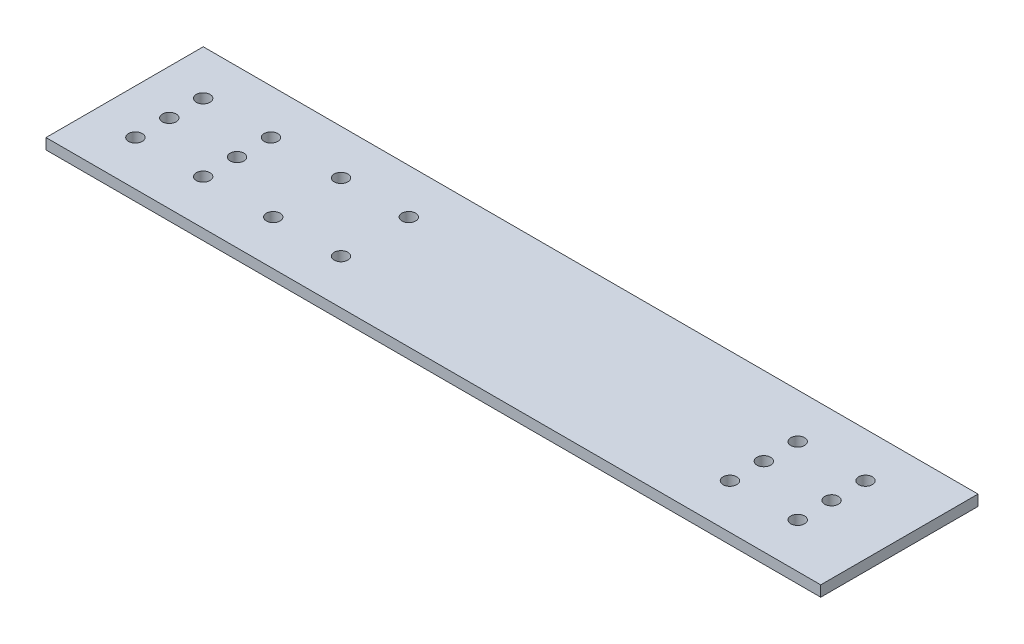
SolidWorks part; units mm, degrees
material "AISI Type A2 Tool Steel"
ref_plane "Front Plane" through (0, 0, 0) normal (0, 0, 1) x (1, 0, 0)
ref_plane "Top Plane" through (0, 0, 0) normal (0, 1, 0) x (1, 0, 0)
ref_plane "Right Plane" through (0, 0, 0) normal (1, 0, 0) x (0, 0, -1)
sketch "Sketch1" plane through (0, 0, 0) normal (0, 1, 0) x (1, 0, 0)
  line L0 (-46.35, 46.4) -> (410.85, 46.4)
  line L1 (-20, 20) -> (20, 20) construction
  line L2 (-20, 20) -> (-20, -20) construction
  line L3 (-20, -20) -> (20, -20) construction
  line L4 (20, 20) -> (20, -20) construction
  line L5 (-20, 20) -> (20, -20) construction
  line L6 (-20, -20) -> (20, 20) construction
  line L8 (-46.35, 46.4) -> (-46.35, -46.4)
  line L11 (410.85, 46.4) -> (410.85, -46.4)
  line L12 (410.85, -46.4) -> (-46.35, -46.4)
  line L13 (350.85, 0) -> (0, 0) construction
  line L14 (370.85, -20) -> (330.85, -20) construction
  line L15 (370.85, -20) -> (370.85, 20) construction
  line L16 (370.85, 20) -> (330.85, 20) construction
  line L17 (330.85, -20) -> (330.85, 20) construction
  line L18 (370.85, -20) -> (330.85, 20) construction
  line L19 (370.85, 20) -> (330.85, -20) construction
  line L20 (81.35, 0) -> (81.35, 30.8998) construction
  line L25 (-40, 40) -> (40, 40) construction
  line L26 (310.85, -40) -> (390.85, -40) construction
  line L31 (-40, 40) -> (-40, -40) construction
  line L32 (-40, -40) -> (40, -40) construction
  line L33 (310.85, -40) -> (310.85, 40) construction
  line L34 (310.85, 40) -> (390.85, 40) construction
  line L35 (390.85, -40) -> (390.85, 40) construction
  line L36 (310.85, -40) -> (390.85, 40) construction
  line L37 (310.85, 40) -> (390.85, -40) construction
  line L38 (278.85, -20) -> (238.85, -20) construction
  line L39 (278.85, -20) -> (278.85, 20) construction
  line L40 (278.85, 20) -> (238.85, 20) construction
  line L41 (238.85, -20) -> (238.85, 20) construction
  line L42 (278.85, -20) -> (238.85, 20) construction
  line L43 (278.85, 20) -> (238.85, -20) construction
  line L48 (40, 40) -> (40, -40) construction
  line L49 (-40, 40) -> (40, -40) construction
  line L50 (-40, -40) -> (40, 40) construction
  line L51 (61.35, -20) -> (101.35, -20) construction
  line L52 (61.35, -20) -> (61.35, 20) construction
  line L53 (61.35, 20) -> (101.35, 20) construction
  line L54 (101.35, -20) -> (101.35, 20) construction
  line L55 (61.35, -20) -> (101.35, 20) construction
  line L56 (61.35, 20) -> (101.35, -20) construction
  line L57 (46.35, 30.8998) -> (116.35, 30.8998) construction
  line L58 (46.35, 30.8998) -> (46.35, -40.05) construction
  line L59 (46.35, -40.05) -> (116.35, -40.05) construction
  line L60 (116.35, 30.8998) -> (116.35, -40.05) construction
  circle A0 centre (-20, 20) radius 4.05
  circle A1 centre (20, 20) radius 4.05
  circle A2 centre (20, -20) radius 4.05
  circle A3 centre (-20, -20) radius 4.05
  circle A4 centre (-20, 0) radius 4.05
  circle A5 centre (20, 0) radius 4.05
  circle A6 centre (330.85, 20) radius 4.05
  circle A8 centre (370.85, 20) radius 4.05
  circle A9 centre (370.85, -20) radius 4.05
  circle A11 centre (330.85, -20) radius 4.05
  circle A20 centre (330.85, 0) radius 4.05
  circle A21 centre (370.85, 0) radius 4.05
  circle A22 centre (278.85, -20) radius 4.05 construction
  circle A23 centre (278.85, 20) radius 4.05 construction
  circle A24 centre (238.85, 20) radius 4.05 construction
  circle A25 centre (238.85, -20) radius 4.05 construction
  circle A26 centre (61.35, 20) radius 4.05
  circle A27 centre (101.35, 20) radius 4.05
  circle A28 centre (101.35, -20) radius 4.05
  circle A29 centre (61.35, -20) radius 4.05
  point P0 (0, 0)
  point P15 (350.85, 0)
  point P29 (258.85, 0)
  point P38 (81.35, 0)
  dimension "D2" = 8.1
  dimension "D8" = 6.35
  dimension "D9" = 46.35
  dimension "D15" = 8.1
  dimension "D18" = 8.1
  dimension "D1" = 40
  dimension "D3" = 80
  dimension "D4" = 46.4
  dimension "D5" = 46.4
  dimension "D6" = 60
  dimension "D7" = 350.85
  dimension "D10" = 40
  dimension "D11" = 80
  dimension "D12" = 80
  dimension "D13" = 40
  dimension "D14" = 40
  dimension "D16" = 32
  dimension "D17" = 457.2
  dimension "D19" = 6.35
  dimension "D20" = 70
  dimension "D21" = 6.35
  dimension "D22" = 41.35
extrude "Boss-Extrude1" add sketch "Sketch1" along normal blind 6.35
